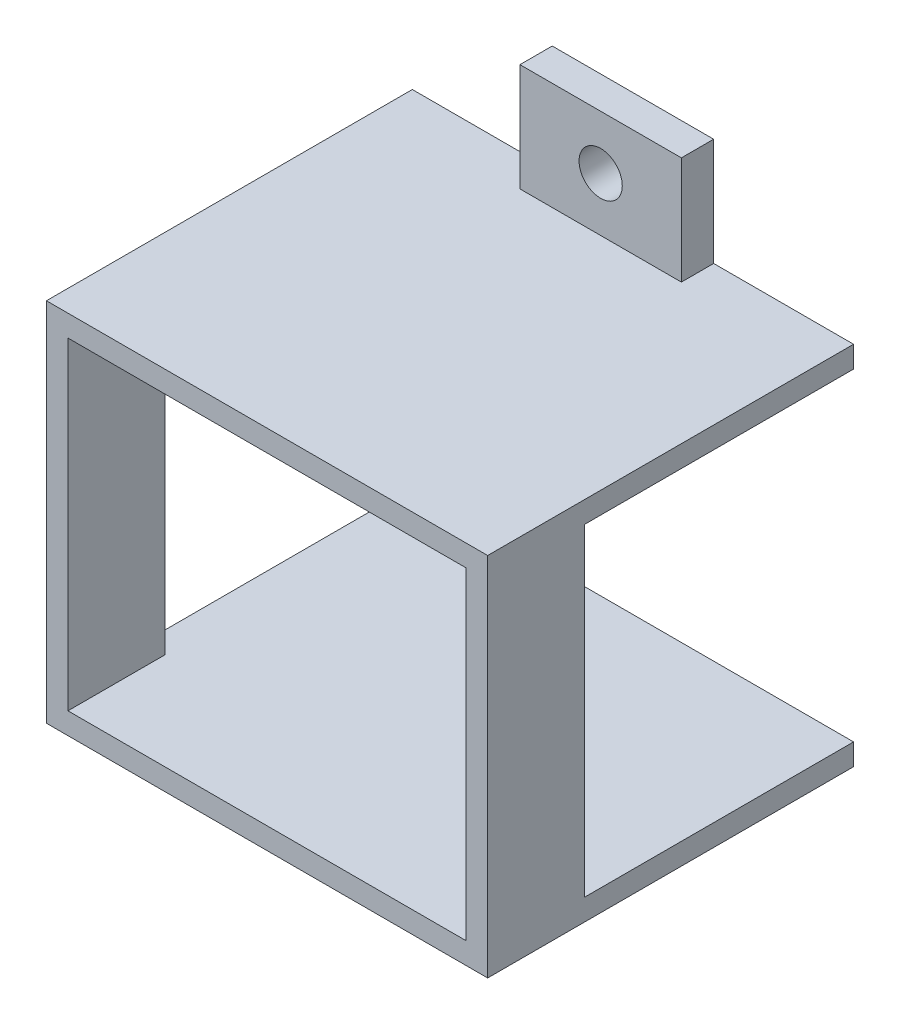
SolidWorks part; units mm, degrees
ref_plane "前基準面" through (0, 0, 0) normal (0, 0, 1) x (1, 0, 0)
ref_plane "上基準面" through (0, 0, 0) normal (0, 1, 0) x (1, 0, 0)
ref_plane "右基準面" through (0, 0, 0) normal (1, 0, 0) x (0, 0, -1)
sketch "草圖1" plane through (0, 0, 0) normal (0, 0, 1) x (1, 0, 0)
  line L1 (-20.5, 17) -> (20.5, 17)
  line L2 (-20.5, 17) -> (-20.5, -17)
  line L3 (-20.5, -17) -> (20.5, -17)
  line L4 (20.5, 17) -> (20.5, -17)
  line L5 (-20.5, 17) -> (20.5, -17) construction
  line L6 (-20.5, -17) -> (20.5, 17) construction
  line L7 (-18.5, 15) -> (18.5, 15)
  line L8 (-18.5, 15) -> (-18.5, -15)
  line L9 (-18.5, -15) -> (18.5, -15)
  line L10 (18.5, 15) -> (18.5, -15)
  line L11 (-18.5, 15) -> (18.5, -15) construction
  line L12 (-18.5, -15) -> (18.5, 15) construction
  point P0 (0, 0)
  point P6 (0, 0)
  dimension "D1" = 41
  dimension "D2" = 34
  dimension "D3" = 37
  dimension "D4" = 30
extrude "填料-伸長1" add sketch "草圖1" along normal blind 34
sketch "草圖2" plane through (0, 17, 0) normal (0, 1, 0) x (1, 0, 0)
  line L0 (20.5, 0) -> (-20.5, 0) construction
  line L1 (-7.5, 0) -> (7.5, 0)
  line L2 (-7.5, 0) -> (-7.5, -3)
  line L3 (-7.5, -3) -> (7.5, -3)
  line L4 (7.5, 0) -> (7.5, -3)
  line L5 (0, 0) -> (0, -3) construction
  dimension "D1" = 3
  dimension "D2" = 15
extrude "填料-伸長2" add sketch "草圖2" along normal blind 10
sketch "草圖3" plane through (0, 0, 3) normal (0, 0, 1) x (1, 0, 0)
  line L0 (7.5, 27) -> (7.5, 17) construction
  line L1 (20.5, 17) -> (-20.5, 17) construction
  circle A0 centre (0, 22) radius 2.0081
  dimension "D1" = 7.5
  dimension "D2" = 5
extrude "除料-伸長1" cut sketch "草圖3" against normal blind 10
mirror "鏡射1" about plane through (0, 0, 0) normal (0, 1, 0) of "填料-伸長2", "除料-伸長1"
sketch "草圖4" plane through (-20.5, 0, 0) normal (-1, 0, 0) x (0, 0, 1)
  line L0 (0, 17) -> (0, -17) construction
  line L1 (0, -15) -> (25, -15)
  line L2 (0, -15) -> (0, 15)
  line L3 (0, 15) -> (25, 15)
  line L4 (25, -15) -> (25, 15)
  line L5 (34, -17) -> (0, -17) construction
  line L6 (34, 17) -> (0, 17) construction
  dimension "D1" = 25
  dimension "D2" = 2
  dimension "D3" = 2
extrude "除料-伸長2" cut sketch "草圖4" against normal blind 60
